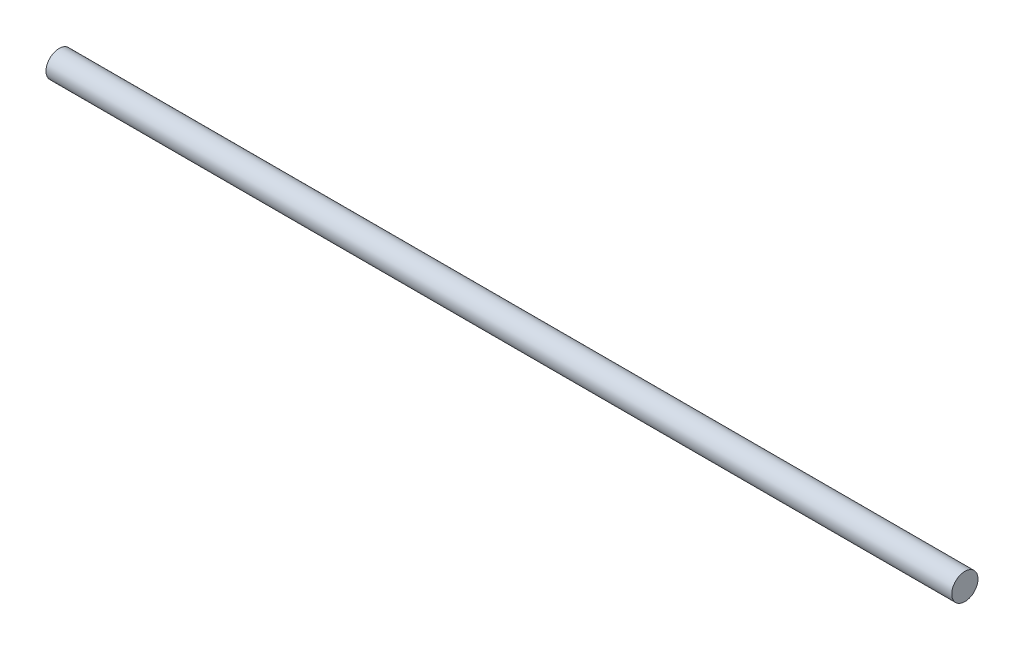
SolidWorks part; units mm, degrees
ref_plane "Спереди" through (0, 0, 0) normal (0, 0, 1) x (1, 0, 0)
ref_plane "Сверху" through (0, 0, 0) normal (0, 1, 0) x (1, 0, 0)
ref_plane "Справа" through (0, 0, 0) normal (1, 0, 0) x (0, 0, -1)
sketch "Эскиз1" plane through (0, 0, 0) normal (1, 0, 0) x (0, 0, -1)
  circle A0 centre (0, 0) radius 4
  dimension "D1" = 8
extrude "Бобышка-Вытянуть1" add sketch "Эскиз1" along normal blind 276
